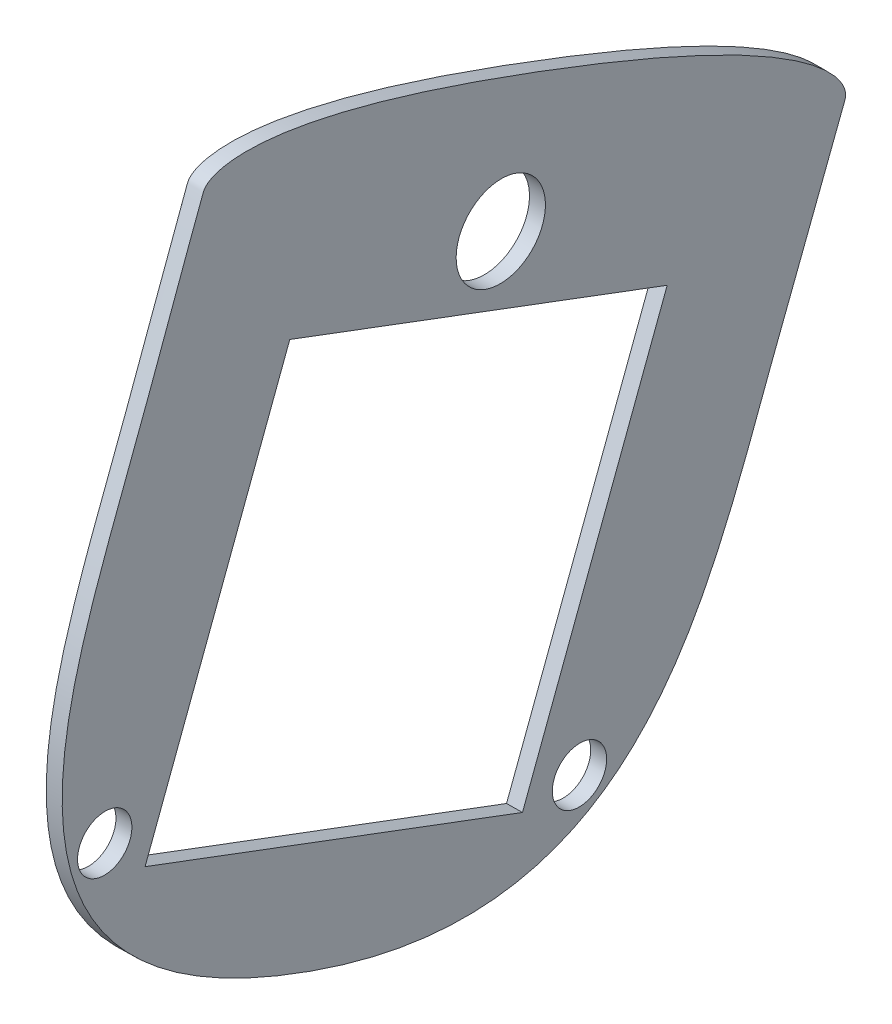
SolidWorks part; units mm, degrees
ref_plane "Front Plane" through (0, 0, 0) normal (0, 0, 1) x (1, 0, 0)
ref_plane "Top Plane" through (0, 0, 0) normal (0, 1, 0) x (1, 0, 0)
ref_plane "Right Plane" through (0, 0, 0) normal (1, 0, 0) x (0, 0, -1)
sketch "Sketch2" plane through (-865.3739, -0.0001, 10.9842) normal (-0.9999, 0, 0.0127) x (0.0127, 0, 0.9999)
  circle A0 centre (-17.1866, -9.2159) radius 6 construction
  circle A1 centre (105.1276, 37.6907) radius 6 construction
  circle A2 centre (-17.1866, -9.2159) radius 6
  circle A3 centre (105.1276, 37.6907) radius 6
  circle A4 centre (2.5155, 122.3361) radius 11.5 construction
  circle A5 centre (2.5155, 122.3361) radius 11.5
  point P0 (86.5551, 152.6282)
  point P1 (81.9504, 150.6796)
  dimension "D4" = 23
  dimension "D1" = 5
ref_plane "Plane1" through (-1179.5486, -0.0001, 14.972) normal (-0.9999, 0, 0.0127) x (0.0127, 0, 0.9999)
sketch "Sketch3" plane through (-1179.5486, -0.0001, 14.972) normal (-0.9999, 0, 0.0127) x (0.0127, 0, 0.9999)
  line L2 (-2.4987, -10.0092) -> (94.7364, 27.2797)
  line L6 (94.7364, 27.2797) -> (57.4475, 124.5149)
  line L7 (57.4475, 124.5149) -> (-39.7876, 87.2259)
  line L8 (-39.7876, 87.2259) -> (-2.4987, -10.0092)
  circle A3 centre (105.1276, 37.6907) radius 7
  circle A8 centre (3.0884, 120.8422) radius 11.5
  circle A9 centre (-17.1866, -9.2159) radius 7
  spline S0 degree 3 poles (84.5877, 169.5548) (84.1591, 170.6141) (83.6114, 171.6458) (82.4825, 172.9682) (81.1275, 174.0328) (79.6255, 174.8519) (78.0481, 175.4677) (75.8837, 176.0674) (73.1375, 176.4938) (69.8483, 176.6685) (66.5932, 176.6095) (63.379, 176.3823) (60.2073, 176.0282) (57.0754, 175.5759) (53.9806, 175.0444) (50.9193, 174.4483) (47.8886, 173.7975) (44.8855, 173.1008) (40.9147, 172.1178) (36.0066, 170.8019) (30.1862, 169.1128) (24.4167, 167.3312) (18.6809, 165.471) (12.9629, 163.5374) (7.2468, 161.5366) (-0.3928, 158.7797) (-6.166, 156.6131) (-13.9483, 153.6286) (-19.6897, 151.3795) (-27.2134, 148.3214) (-32.8014, 145.9872) (-38.3459, 143.6017) (-43.8547, 141.1498) (-49.3359, 138.6168) (-54.7932, 135.9811) (-59.3225, 133.6777) (-62.9324, 131.7536) (-65.6313, 130.2638) (-68.3201, 128.7213) (-70.995, 127.1176) (-73.6517, 125.4434) (-76.283, 123.6856) (-78.8782, 121.8282) (-81.4203, 119.8479) (-83.8804, 117.7153) (-86.2094, 115.386) (-87.9665, 113.2326) (-89.1751, 111.3395) (-89.9363, 109.8267) (-90.5056, 108.2133) (-90.8014, 106.5155) (-90.7567, 104.7772) (-90.474, 103.6437) (-90.0844, 102.5695) (-89.841, 101.912) (-89.5415, 101.1241) (-89.3902, 100.7305) (-89.238, 100.337) (-89.086, 99.9434) (-88.9335, 99.5497) (-88.7301, 99.0246) (-88.3735, 98.1053) (-87.8622, 96.7909) (-87.2459, 95.2119) (-86.6271, 93.6311) (-86.006, 92.0484) (-85.3828, 90.4637) (-84.7576, 88.8772) (-84.1306, 87.2885) (-83.5021, 85.6979) (-82.662, 83.5742) (-81.6087, 80.9142) (-80.341, 77.7134) (-79.0707, 74.5033) (-77.7994, 71.2836) (-76.5287, 68.0539) (-75.2594, 64.814) (-73.9927, 61.5637) (-72.7309, 58.3024) (-71.4763, 55.0294) (-69.81, 50.6514) (-67.733, 45.1559) (-65.1929, 38.5485) (-63.0021, 33.047) (-61.1797, 28.6615) (-60.0063, 25.9297) (-59.0438, 23.7513) (-58.3093, 22.1218) (-57.5611, 20.497) (-56.7986, 18.8776) (-56.0207, 17.2642) (-55.227, 15.6574) (-54.4159, 14.0579) (-52.7551, 10.8759) (-50.1136, 6.1705) (-46.2141, 0.1062) (-41.8798, -5.6826) (-37.071, -11.0955) (-31.7493, -16.031) (-26.8927, -19.6435) (-22.7717, -22.1827) (-18.509, -24.4734) (-12.9357, -26.8488) (-5.9687, -28.8976) (1.1735, -30.1678) (8.3946, -30.7243) (15.6292, -30.6392) (22.8222, -29.9927) (29.9449, -28.8562) (36.9714, -27.3105) (46.201, -24.7823) (52.9582, -22.4509) (61.8197, -19.0525) (68.4041, -16.2675) (76.9584, -11.9755) (83.2171, -8.426) (89.2737, -4.508) (95.0546, -0.1787) (100.4909, 4.596) (105.488, 9.8386) (109.9491, 15.5591) (113.7592, 21.7413) (116.3146, 27.2342) (117.9522, 31.7877) (119.3182, 36.4313) (120.5136, 42.3647) (121.1702, 49.5927) (121.1263, 56.8326) (120.4783, 64.0347) (119.3229, 71.151) (118.1408, 76.4157) (117.2481, 79.8921) (116.7817, 81.6236) (116.2975, 83.349) (115.7971, 85.0687) (115.2813, 86.7826) (114.7512, 88.4909) (114.2078, 90.1937) (113.467, 92.4568) (112.5129, 95.2725) (110.9356, 99.7518) (108.8862, 105.3072) (106.3571, 111.9184) (104.227, 117.3933) (102.5388, 121.7627) (101.2832, 125.0351) (100.0408, 128.3038) (98.8095, 131.5676) (97.5869, 134.8253) (96.3723, 138.0765) (95.1647, 141.3206) (93.9629, 144.5568) (92.7653, 147.7846) (91.7699, 150.4668) (90.9746, 152.6077) (90.3784, 154.2108) (89.7824, 155.8113) (89.1863, 157.4091) (88.5902, 159.0041) (87.9938, 160.5963) (87.3968, 162.1856) (86.7993, 163.7719) (86.3006, 165.0911) (85.9511, 166.0132) (85.7512, 166.5397) (85.6013, 166.9344) (85.4511, 167.3288) (85.3012, 167.7231) (85.1505, 168.117) (84.8464, 168.9032) (84.5877, 169.5548) (84.1591, 170.6141) (83.6114, 171.6458) knots -0.00321 -0.002568 0 0 0.002678 0.005356 0.008033 0.010711 0.013389 0.016067 0.021422 0.026778 0.032133 0.037489 0.042844 0.0482 0.053555 0.058911 0.064266 0.069622 0.074977 0.085688 0.096399 0.10711 0.117821 0.128532 0.139243 0.149955 0.171377 0.171377 0.192798 0.203509 0.21422 0.224931 0.235641 0.246352 0.257063 0.267774 0.273129 0.278485 0.28384 0.289196 0.294551 0.299906 0.305262 0.310617 0.315973 0.321328 0.326683 0.329361 0.332039 0.334717 0.337394 0.340072 0.34275 0.34275 0.345317 0.345958 0.3466 0.347242 0.347884 0.348525 0.349167 0.350451 0.353018 0.355585 0.358152 0.360719 0.363286 0.365853 0.36842 0.370987 0.373554 0.378688 0.383822 0.388956 0.39409 0.399224 0.404358 0.409492 0.414626 0.419761 0.424895 0.435163 0.445431 0.455699 0.460833 0.465967 0.468534 0.471101 0.473668 0.476235 0.478802 0.481369 0.483936 0.486503 0.496771 0.507039 0.517308 0.527576 0.537844 0.548112 0.553246 0.55838 0.568648 0.578916 0.589184 0.599453 0.609721 0.619989 0.630257 0.640525 0.650793 0.671329 0.671329 0.691871 0.702142 0.712413 0.722684 0.732955 0.743226 0.753497 0.763768 0.774039 0.78431 0.789445 0.794581 0.804852 0.815123 0.825394 0.835665 0.845936 0.856207 0.858774 0.861342 0.86391 0.866478 0.869045 0.871613 0.874181 0.876748 0.881884 0.887019 0.89729 0.907561 0.917832 0.922968 0.928103 0.933239 0.938374 0.94351 0.948645 0.953781 0.958916 0.964052 0.969187 0.971755 0.974323 0.97689 0.979458 0.982026 0.984594 0.987161 0.989729 0.992297 0.993581 0.994223 0.994865 0.995506 0.996148 0.99679 0.997432 1 1 1.002678 1.005356 1.008033 only from (84.3779, 170.0733) to (84.3779, 170.0733)
  spline S1 degree 3 poles (84.5877, 169.5548) (84.1591, 170.6141) (83.6114, 171.6458) (82.4825, 172.9682) (81.1275, 174.0328) (79.6255, 174.8519) (78.0481, 175.4677) (75.8837, 176.0674) (73.1375, 176.4938) (69.8483, 176.6685) (66.5932, 176.6095) (63.379, 176.3823) (60.2073, 176.0282) (57.0754, 175.5759) (53.9806, 175.0444) (50.9193, 174.4483) (47.8886, 173.7975) (44.8855, 173.1008) (40.9147, 172.1178) (36.0066, 170.8019) (30.1862, 169.1128) (24.4167, 167.3312) (18.6809, 165.471) (12.9629, 163.5374) (7.2468, 161.5366) (-0.3928, 158.7797) (-6.166, 156.6131) (-13.9483, 153.6286) (-19.6897, 151.3795) (-27.2134, 148.3214) (-32.8014, 145.9872) (-38.3459, 143.6017) (-43.8547, 141.1498) (-49.3359, 138.6168) (-54.7932, 135.9811) (-59.3225, 133.6777) (-62.9324, 131.7536) (-65.6313, 130.2638) (-68.3201, 128.7213) (-70.995, 127.1176) (-73.6517, 125.4434) (-76.283, 123.6856) (-78.8782, 121.8282) (-81.4203, 119.8479) (-83.8804, 117.7153) (-86.2094, 115.386) (-87.9665, 113.2326) (-89.1751, 111.3395) (-89.9363, 109.8267) (-90.5056, 108.2133) (-90.8014, 106.5155) (-90.7567, 104.7772) (-90.474, 103.6437) (-90.0844, 102.5695) (-89.841, 101.912) (-89.5415, 101.1241) (-89.3902, 100.7305) (-89.238, 100.337) (-89.086, 99.9434) (-88.9335, 99.5497) (-88.7301, 99.0246) (-88.3735, 98.1053) (-87.8622, 96.7909) (-87.2459, 95.2119) (-86.6271, 93.6311) (-86.006, 92.0484) (-85.3828, 90.4637) (-84.7576, 88.8772) (-84.1306, 87.2885) (-83.5021, 85.6979) (-82.662, 83.5742) (-81.6087, 80.9142) (-80.341, 77.7134) (-79.0707, 74.5033) (-77.7994, 71.2836) (-76.5287, 68.0539) (-75.2594, 64.814) (-73.9927, 61.5637) (-72.7309, 58.3024) (-71.4763, 55.0294) (-69.81, 50.6514) (-67.733, 45.1559) (-65.1929, 38.5485) (-63.0021, 33.047) (-61.1797, 28.6615) (-60.0063, 25.9297) (-59.0438, 23.7513) (-58.3093, 22.1218) (-57.5611, 20.497) (-56.7986, 18.8776) (-56.0207, 17.2642) (-55.227, 15.6574) (-54.4159, 14.0579) (-52.7551, 10.8759) (-50.1136, 6.1705) (-46.2141, 0.1062) (-41.8798, -5.6826) (-37.071, -11.0955) (-31.7493, -16.031) (-26.8927, -19.6435) (-22.7717, -22.1827) (-18.509, -24.4734) (-12.9357, -26.8488) (-5.9687, -28.8976) (1.1735, -30.1678) (8.3946, -30.7243) (15.6292, -30.6392) (22.8222, -29.9927) (29.9449, -28.8562) (36.9714, -27.3105) (46.201, -24.7823) (52.9582, -22.4509) (61.8197, -19.0525) (68.4041, -16.2675) (76.9584, -11.9755) (83.2171, -8.426) (89.2737, -4.508) (95.0546, -0.1787) (100.4909, 4.596) (105.488, 9.8386) (109.9491, 15.5591) (113.7592, 21.7413) (116.3146, 27.2342) (117.9522, 31.7877) (119.3182, 36.4313) (120.5136, 42.3647) (121.1702, 49.5927) (121.1263, 56.8326) (120.4783, 64.0347) (119.3229, 71.151) (118.1408, 76.4157) (117.2481, 79.8921) (116.7817, 81.6236) (116.2975, 83.349) (115.7971, 85.0687) (115.2813, 86.7826) (114.7512, 88.4909) (114.2078, 90.1937) (113.467, 92.4568) (112.5129, 95.2725) (110.9356, 99.7518) (108.8862, 105.3072) (106.3571, 111.9184) (104.227, 117.3933) (102.5388, 121.7627) (101.2832, 125.0351) (100.0408, 128.3038) (98.8095, 131.5676) (97.5869, 134.8253) (96.3723, 138.0765) (95.1647, 141.3206) (93.9629, 144.5568) (92.7653, 147.7846) (91.7699, 150.4668) (90.9746, 152.6077) (90.3784, 154.2108) (89.7824, 155.8113) (89.1863, 157.4091) (88.5902, 159.0041) (87.9938, 160.5963) (87.3968, 162.1856) (86.7993, 163.7719) (86.3006, 165.0911) (85.9511, 166.0132) (85.7512, 166.5397) (85.6013, 166.9344) (85.4511, 167.3288) (85.3012, 167.7231) (85.1505, 168.117) (84.8464, 168.9032) (84.5877, 169.5548) (84.1591, 170.6141) (83.6114, 171.6458) knots -0.00321 -0.002568 0 0 0.002678 0.005356 0.008033 0.010711 0.013389 0.016067 0.021422 0.026778 0.032133 0.037489 0.042844 0.0482 0.053555 0.058911 0.064266 0.069622 0.074977 0.085688 0.096399 0.10711 0.117821 0.128532 0.139243 0.149955 0.171377 0.171377 0.192798 0.203509 0.21422 0.224931 0.235641 0.246352 0.257063 0.267774 0.273129 0.278485 0.28384 0.289196 0.294551 0.299906 0.305262 0.310617 0.315973 0.321328 0.326683 0.329361 0.332039 0.334717 0.337394 0.340072 0.34275 0.34275 0.345317 0.345958 0.3466 0.347242 0.347884 0.348525 0.349167 0.350451 0.353018 0.355585 0.358152 0.360719 0.363286 0.365853 0.36842 0.370987 0.373554 0.378688 0.383822 0.388956 0.39409 0.399224 0.404358 0.409492 0.414626 0.419761 0.424895 0.435163 0.445431 0.455699 0.460833 0.465967 0.468534 0.471101 0.473668 0.476235 0.478802 0.481369 0.483936 0.486503 0.496771 0.507039 0.517308 0.527576 0.537844 0.548112 0.553246 0.55838 0.568648 0.578916 0.589184 0.599453 0.609721 0.619989 0.630257 0.640525 0.650793 0.671329 0.671329 0.691871 0.702142 0.712413 0.722684 0.732955 0.743226 0.753497 0.763768 0.774039 0.78431 0.789445 0.794581 0.804852 0.815123 0.825394 0.835665 0.845936 0.856207 0.858774 0.861342 0.86391 0.866478 0.869045 0.871613 0.874181 0.876748 0.881884 0.887019 0.89729 0.907561 0.917832 0.922968 0.928103 0.933239 0.938374 0.94351 0.948645 0.953781 0.958916 0.964052 0.969187 0.971755 0.974323 0.97689 0.979458 0.982026 0.984594 0.987161 0.989729 0.992297 0.993581 0.994223 0.994865 0.995506 0.996148 0.99679 0.997432 1 1 1.002678 1.005356 1.008033 only from (84.3779, 170.0733) to (84.3779, 170.0733)
  spline S2 degree 3 poles (79.7703, 168.0973) (79.654, 168.385) (79.5608, 168.567) (79.34, 168.909) (79.2107, 169.0695) (78.782, 169.5156) (78.4531, 169.7564) (77.7463, 170.1738) (77.3742, 170.347) (76.6181, 170.646) (76.2313, 170.7718) (75.4457, 170.9901) (75.0459, 171.0829) (74.2475, 171.2414) (73.8476, 171.3072) (72.6462, 171.473) (71.8432, 171.5429) (69.4298, 171.6691) (67.8151, 171.6433) (64.5792, 171.4656) (62.9671, 171.312) (59.7615, 170.9206) (58.1658, 170.6823) (54.9849, 170.1436) (53.3996, 169.8431) (48.656, 168.8688) (45.5068, 168.1227) (39.2498, 166.5091) (36.1403, 165.6406) (29.9484, 163.8155) (26.8662, 162.8586) (17.65, 159.8886) (11.5458, 157.7754) (-0.6049, 153.3792) (-6.6499, 151.0973) (-18.6886, 146.4029) (-24.6805, 143.9847) (-36.5791, 138.946) (-42.4872, 136.3273) (-51.2341, 132.1553) (-54.1301, 130.7232) (-59.8634, 127.7454) (-62.7011, 126.2002) (-66.8856, 123.7579) (-68.2675, 122.9231) (-70.9987, 121.2004) (-72.3487, 120.3119) (-74.9994, 118.4656) (-76.2997, 117.5087) (-78.8252, 115.4929) (-80.0492, 114.4377) (-81.7749, 112.7382) (-82.3328, 112.1498) (-83.3836, 110.9299) (-83.8771, 110.2969) (-84.5427, 109.2937) (-84.7517, 108.95) (-85.1321, 108.2356) (-85.3048, 107.8624) (-85.5131, 107.2891) (-85.5741, 107.0954) (-85.6734, 106.7005) (-85.7118, 106.4978) (-85.7567, 106.0923) (-85.7631, 105.8894) (-85.7375, 105.4833) (-85.7033, 105.2783) (-85.5978, 104.885) (-85.5239, 104.6959) (-85.3844, 104.3148) (-85.3142, 104.1244) (-85.1021, 103.5537) (-84.9587, 103.174) (-84.5227, 102.0368) (-84.2284, 101.28) (-83.3473, 99.0091) (-82.7572, 97.4963) (-77.4279, 83.8874) (-72.5683, 71.8388) (-66.7371, 56.6822) (-65.5847, 53.6454) (-63.2813, 47.5713) (-62.1268, 44.5353) (-59.771, 38.4819) (-58.5707, 35.464) (-56.7026, 30.9639) (-56.0686, 29.4684) (-54.7723, 26.4884) (-54.1097, 25.0035) (-50.7192, 17.6341) (-47.7589, 11.8968) (-42.5832, 3.7604) (-40.7366, 1.1258) (-37.7313, -2.6759) (-36.6901, -3.9179) (-35.0604, -5.7377) (-34.5059, -6.337) (-33.3724, -7.5201) (-32.7922, -8.1052) (-29.8441, -10.9713) (-27.345, -13.0666) (-23.3611, -15.8788) (-21.9939, -16.761) (-19.1769, -18.4096) (-17.7261, -19.1766) (-10.2663, -22.7) (-3.9825, -24.3776) (3.3729, -25.2321) (4.1924, -25.3124) (5.8269, -25.4445) (6.6433, -25.4963) (9.09, -25.6118) (10.7178, -25.6352) (15.5924, -25.5618) (18.8302, -25.3221) (23.6723, -24.7256) (25.2838, -24.487) (28.5025, -23.9384) (30.1115, -23.628) (34.9193, -22.6026) (38.0868, -21.7953) (44.3622, -19.9846) (47.4703, -18.982) (52.0947, -17.3537) (53.6299, -16.7903) (56.6886, -15.6251) (58.2124, -15.0236) (62.7493, -13.1641) (65.733, -11.8489) (71.6057, -9.0437) (74.4945, -7.5535) (80.1538, -4.3544) (82.9251, -2.6472) (86.9704, 0.1194) (88.3001, 1.0763) (90.263, 2.5701) (90.9119, 3.0777) (92.1913, 4.1078) (92.8227, 4.6309) (95.9368, 7.2882) (98.2906, 9.5479) (101.5765, 13.1758) (102.631, 14.4249) (104.1451, 16.3643) (104.6385, 17.0217) (105.6014, 18.3598) (106.0705, 19.0401) (108.3321, 22.4686) (109.8916, 25.3227) (112.4961, 31.2603) (113.5391, 34.3445) (114.5167, 38.3452) (114.696, 39.1533) (115.0193, 40.7681) (115.1639, 41.5767) (115.5483, 44.0063) (115.7388, 45.6309) (116.1311, 50.5177) (116.1533, 53.7931) (115.9328, 57.9055) (115.8763, 58.7278) (115.7406, 60.3643) (115.6615, 61.1797) (115.3922, 63.6178) (115.1705, 65.2327) (114.3953, 70.0494) (113.7318, 73.2236) (112.1864, 79.5171) (111.3038, 82.6361) (109.3954, 88.8382) (108.3675, 91.9207) (106.215, 98.0612) (105.0894, 101.1202) (102.7905, 107.2203) (101.6164, 110.261) (99.26, 116.3391) (98.0812, 119.3779) (95.7512, 125.4661) (94.5998, 128.5155) (91.1648, 137.6705) (88.9043, 143.7849) (85.4993, 152.9511) (84.362, 156.0057) (82.6444, 160.5831) (82.0699, 162.1082) (81.2041, 164.3942) (80.9151, 165.1561) (80.4796, 166.2982) (80.3329, 166.6783) (80.1095, 167.2472) (79.9971, 167.5314) (79.8836, 167.8152) (79.8078, 168.0043) (79.7703, 168.0973) (79.654, 168.385) (79.5608, 168.567) knots -0.000488 -0.000488 0 0 0.000977 0.000977 0.001953 0.001953 0.003906 0.003906 0.005859 0.005859 0.007812 0.007812 0.009766 0.009766 0.011719 0.011719 0.015625 0.015625 0.023437 0.023437 0.03125 0.03125 0.039062 0.039062 0.046875 0.046875 0.0625 0.0625 0.078125 0.078125 0.09375 0.09375 0.125 0.125 0.15625 0.15625 0.1875 0.1875 0.21875 0.21875 0.234375 0.234375 0.25 0.25 0.257812 0.257812 0.265625 0.265625 0.273437 0.273437 0.28125 0.28125 0.285156 0.285156 0.289062 0.289062 0.291016 0.291016 0.292969 0.292969 0.293945 0.293945 0.294922 0.294922 0.295898 0.295898 0.296875 0.296875 0.297852 0.297852 0.298828 0.298828 0.300781 0.300781 0.304687 0.304687 0.3125 0.3125 0.375 0.375 0.390625 0.390625 0.40625 0.40625 0.421875 0.421875 0.429687 0.429687 0.4375 0.4375 0.46875 0.46875 0.484375 0.484375 0.492187 0.492187 0.496094 0.496094 0.5 0.5 0.515625 0.515625 0.523437 0.523437 0.53125 0.53125 0.5625 0.5625 0.566406 0.566406 0.570312 0.570312 0.578125 0.578125 0.59375 0.59375 0.601562 0.601562 0.609375 0.609375 0.625 0.625 0.640625 0.640625 0.648437 0.648437 0.65625 0.65625 0.671875 0.671875 0.6875 0.6875 0.703125 0.703125 0.710937 0.710937 0.714844 0.714844 0.71875 0.71875 0.734375 0.734375 0.742187 0.742187 0.746094 0.746094 0.75 0.75 0.765625 0.765625 0.78125 0.78125 0.785156 0.785156 0.789062 0.789062 0.796875 0.796875 0.8125 0.8125 0.816406 0.816406 0.820312 0.820312 0.828125 0.828125 0.84375 0.84375 0.859375 0.859375 0.875 0.875 0.890625 0.890625 0.90625 0.90625 0.921875 0.921875 0.9375 0.9375 0.96875 0.96875 0.984375 0.984375 0.992187 0.992187 0.996094 0.996094 0.998047 0.998047 0.999023 0.999512 0.999512 1 1 1.000977 1.000977 1.001953 only from (79.7315, 168.1932) to (79.7315, 168.1932)
  spline S3 degree 3 poles (79.7703, 168.0973) (79.654, 168.385) (79.5608, 168.567) (79.34, 168.909) (79.2107, 169.0695) (78.782, 169.5156) (78.4531, 169.7564) (77.7463, 170.1738) (77.3742, 170.347) (76.6181, 170.646) (76.2313, 170.7718) (75.4457, 170.9901) (75.0459, 171.0829) (74.2475, 171.2414) (73.8476, 171.3072) (72.6462, 171.473) (71.8432, 171.5429) (69.4298, 171.6691) (67.8151, 171.6433) (64.5792, 171.4656) (62.9671, 171.312) (59.7615, 170.9206) (58.1658, 170.6823) (54.9849, 170.1436) (53.3996, 169.8431) (48.656, 168.8688) (45.5068, 168.1227) (39.2498, 166.5091) (36.1403, 165.6406) (29.9484, 163.8155) (26.8662, 162.8586) (17.65, 159.8886) (11.5458, 157.7754) (-0.6049, 153.3792) (-6.6499, 151.0973) (-18.6886, 146.4029) (-24.6805, 143.9847) (-36.5791, 138.946) (-42.4872, 136.3273) (-51.2341, 132.1553) (-54.1301, 130.7232) (-59.8634, 127.7454) (-62.7011, 126.2002) (-66.8856, 123.7579) (-68.2675, 122.9231) (-70.9987, 121.2004) (-72.3487, 120.3119) (-74.9994, 118.4656) (-76.2997, 117.5087) (-78.8252, 115.4929) (-80.0492, 114.4377) (-81.7749, 112.7382) (-82.3328, 112.1498) (-83.3836, 110.9299) (-83.8771, 110.2969) (-84.5427, 109.2937) (-84.7517, 108.95) (-85.1321, 108.2356) (-85.3048, 107.8624) (-85.5131, 107.2891) (-85.5741, 107.0954) (-85.6734, 106.7005) (-85.7118, 106.4978) (-85.7567, 106.0923) (-85.7631, 105.8894) (-85.7375, 105.4833) (-85.7033, 105.2783) (-85.5978, 104.885) (-85.5239, 104.6959) (-85.3844, 104.3148) (-85.3142, 104.1244) (-85.1021, 103.5537) (-84.9587, 103.174) (-84.5227, 102.0368) (-84.2284, 101.28) (-83.3473, 99.0091) (-82.7572, 97.4963) (-77.4279, 83.8874) (-72.5683, 71.8388) (-66.7371, 56.6822) (-65.5847, 53.6454) (-63.2813, 47.5713) (-62.1268, 44.5353) (-59.771, 38.4819) (-58.5707, 35.464) (-56.7026, 30.9639) (-56.0686, 29.4684) (-54.7723, 26.4884) (-54.1097, 25.0035) (-50.7192, 17.6341) (-47.7589, 11.8968) (-42.5832, 3.7604) (-40.7366, 1.1258) (-37.7313, -2.6759) (-36.6901, -3.9179) (-35.0604, -5.7377) (-34.5059, -6.337) (-33.3724, -7.5201) (-32.7922, -8.1052) (-29.8441, -10.9713) (-27.345, -13.0666) (-23.3611, -15.8788) (-21.9939, -16.761) (-19.1769, -18.4096) (-17.7261, -19.1766) (-10.2663, -22.7) (-3.9825, -24.3776) (3.3729, -25.2321) (4.1924, -25.3124) (5.8269, -25.4445) (6.6433, -25.4963) (9.09, -25.6118) (10.7178, -25.6352) (15.5924, -25.5618) (18.8302, -25.3221) (23.6723, -24.7256) (25.2838, -24.487) (28.5025, -23.9384) (30.1115, -23.628) (34.9193, -22.6026) (38.0868, -21.7953) (44.3622, -19.9846) (47.4703, -18.982) (52.0947, -17.3537) (53.6299, -16.7903) (56.6886, -15.6251) (58.2124, -15.0236) (62.7493, -13.1641) (65.733, -11.8489) (71.6057, -9.0437) (74.4945, -7.5535) (80.1538, -4.3544) (82.9251, -2.6472) (86.9704, 0.1194) (88.3001, 1.0763) (90.263, 2.5701) (90.9119, 3.0777) (92.1913, 4.1078) (92.8227, 4.6309) (95.9368, 7.2882) (98.2906, 9.5479) (101.5765, 13.1758) (102.631, 14.4249) (104.1451, 16.3643) (104.6385, 17.0217) (105.6014, 18.3598) (106.0705, 19.0401) (108.3321, 22.4686) (109.8916, 25.3227) (112.4961, 31.2603) (113.5391, 34.3445) (114.5167, 38.3452) (114.696, 39.1533) (115.0193, 40.7681) (115.1639, 41.5767) (115.5483, 44.0063) (115.7388, 45.6309) (116.1311, 50.5177) (116.1533, 53.7931) (115.9328, 57.9055) (115.8763, 58.7278) (115.7406, 60.3643) (115.6615, 61.1797) (115.3922, 63.6178) (115.1705, 65.2327) (114.3953, 70.0494) (113.7318, 73.2236) (112.1864, 79.5171) (111.3038, 82.6361) (109.3954, 88.8382) (108.3675, 91.9207) (106.215, 98.0612) (105.0894, 101.1202) (102.7905, 107.2203) (101.6164, 110.261) (99.26, 116.3391) (98.0812, 119.3779) (95.7512, 125.4661) (94.5998, 128.5155) (91.1648, 137.6705) (88.9043, 143.7849) (85.4993, 152.9511) (84.362, 156.0057) (82.6444, 160.5831) (82.0699, 162.1082) (81.2041, 164.3942) (80.9151, 165.1561) (80.4796, 166.2982) (80.3329, 166.6783) (80.1095, 167.2472) (79.9971, 167.5314) (79.8836, 167.8152) (79.8078, 168.0043) (79.7703, 168.0973) (79.654, 168.385) (79.5608, 168.567) knots -0.000488 -0.000488 0 0 0.000977 0.000977 0.001953 0.001953 0.003906 0.003906 0.005859 0.005859 0.007812 0.007812 0.009766 0.009766 0.011719 0.011719 0.015625 0.015625 0.023437 0.023437 0.03125 0.03125 0.039062 0.039062 0.046875 0.046875 0.0625 0.0625 0.078125 0.078125 0.09375 0.09375 0.125 0.125 0.15625 0.15625 0.1875 0.1875 0.21875 0.21875 0.234375 0.234375 0.25 0.25 0.257812 0.257812 0.265625 0.265625 0.273437 0.273437 0.28125 0.28125 0.285156 0.285156 0.289062 0.289062 0.291016 0.291016 0.292969 0.292969 0.293945 0.293945 0.294922 0.294922 0.295898 0.295898 0.296875 0.296875 0.297852 0.297852 0.298828 0.298828 0.300781 0.300781 0.304687 0.304687 0.3125 0.3125 0.375 0.375 0.390625 0.390625 0.40625 0.40625 0.421875 0.421875 0.429687 0.429687 0.4375 0.4375 0.46875 0.46875 0.484375 0.484375 0.492187 0.492187 0.496094 0.496094 0.5 0.5 0.515625 0.515625 0.523437 0.523437 0.53125 0.53125 0.5625 0.5625 0.566406 0.566406 0.570312 0.570312 0.578125 0.578125 0.59375 0.59375 0.601562 0.601562 0.609375 0.609375 0.625 0.625 0.640625 0.640625 0.648437 0.648437 0.65625 0.65625 0.671875 0.671875 0.6875 0.6875 0.703125 0.703125 0.710937 0.710937 0.714844 0.714844 0.71875 0.71875 0.734375 0.734375 0.742187 0.742187 0.746094 0.746094 0.75 0.75 0.765625 0.765625 0.78125 0.78125 0.785156 0.785156 0.789062 0.789062 0.796875 0.796875 0.8125 0.8125 0.816406 0.816406 0.820312 0.820312 0.828125 0.828125 0.84375 0.84375 0.859375 0.859375 0.875 0.875 0.890625 0.890625 0.90625 0.90625 0.921875 0.921875 0.9375 0.9375 0.96875 0.96875 0.984375 0.984375 0.992187 0.992187 0.996094 0.996094 0.998047 0.998047 0.999023 0.999512 0.999512 1 1 1.000977 1.000977 1.001953 only from (79.7315, 168.1932) to (79.7315, 168.1932)
extrude "Boss-Extrude1" add sketch "Sketch3" against normal blind 4
